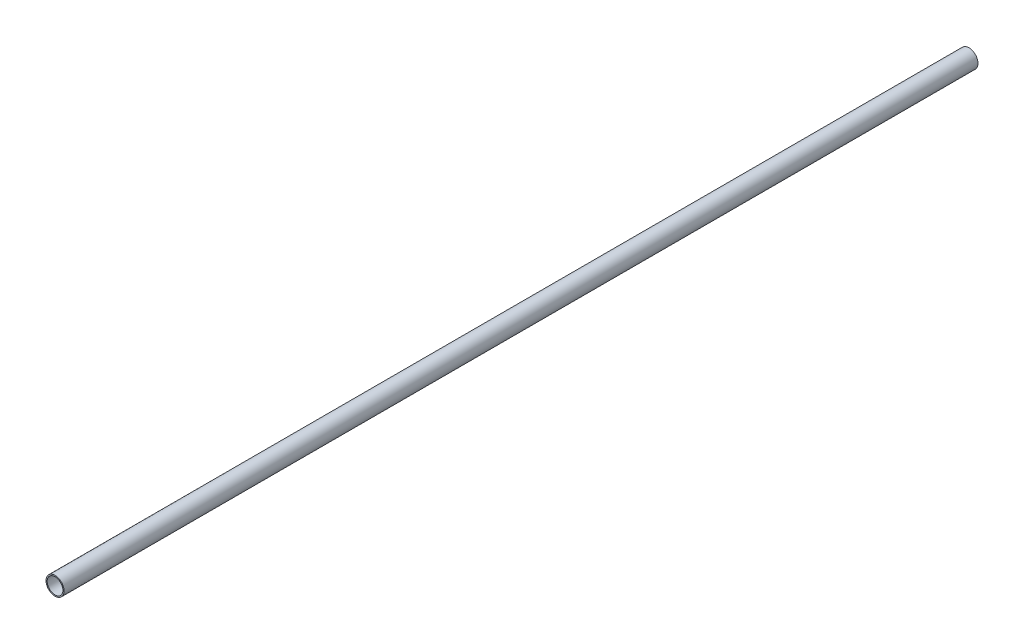
SolidWorks part; units mm, degrees
ref_plane "Front Plane" through (0, 0, 0) normal (0, 0, 1) x (1, 0, 0)
ref_plane "Top Plane" through (0, 0, 0) normal (0, 1, 0) x (1, 0, 0)
ref_plane "Right Plane" through (0, 0, 0) normal (1, 0, 0) x (0, 0, -1)
sketch "Sketch1" plane through (0, 0, 0) normal (0, 0, 1) x (1, 0, 0)
  circle A0 centre (0, 0) radius 30.1625
  circle A1 centre (0, 0) radius 26.2509
  dimension "D1" = 60.325
  dimension "D2" = 3.9116
extrude "Boss-Extrude1" add sketch "Sketch1" along normal blind 3048
